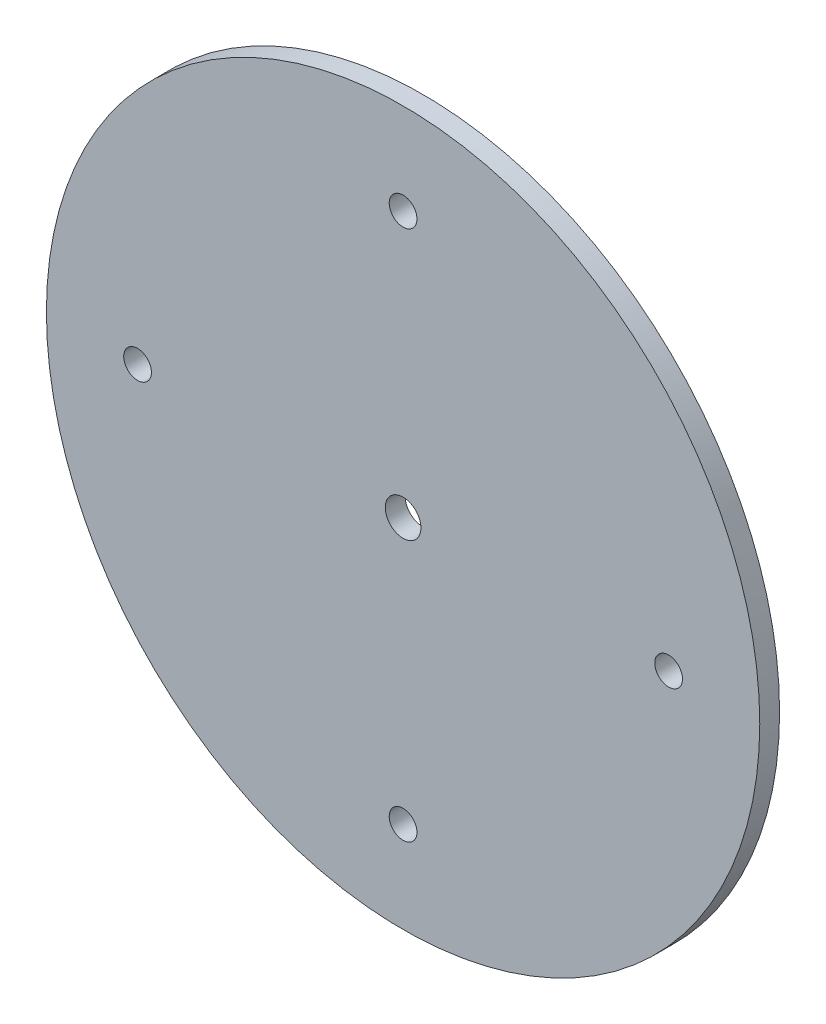
SolidWorks part; units mm, degrees
ref_plane "Front Plane" through (0, 0, 0) normal (0, 0, 1) x (1, 0, 0)
ref_plane "Top Plane" through (0, 0, 0) normal (0, 1, 0) x (1, 0, 0)
ref_plane "Right Plane" through (0, 0, 0) normal (1, 0, 0) x (0, 0, -1)
sketch "Sketch1" plane through (0, 0, 0) normal (0, 0, 1) x (1, 0, 0)
  line L0 (0, 0) -> (0, 33.5) construction
  line L1 (0, 33.5) -> (0, 45) construction
  circle A0 centre (0, 0) radius 45
  circle A1 centre (0, 0) radius 2.25
  circle A2 centre (0, 33.5) radius 1.75
  circle A3 centre (33.5, 0) radius 1.75
  circle A4 centre (0, -33.5) radius 1.75
  circle A5 centre (-33.5, 0) radius 1.75
  point P7 (0, 0)
  point P8 (0, 0)
  point P9 (0, 0)
  point P16 (0, 0)
  dimension "D1" = 3.5
  dimension "D2" = 4.5
  dimension "D3" = 90
  dimension "D4" = 33.5
  dimension "D5" = 4
extrude "Boss-Extrude1" add sketch "Sketch1" along normal blind 2.5
sketch "Sketch2" plane through (0, 0, 0) normal (0, 0, -1) x (-1, 0, 0)
  circle A0 centre (0, 0) radius 29.85
  circle A1 centre (0, 0) radius 12.65
  dimension "D1" = 59.7
  dimension "D2" = 25.3
extrude "Boss-Extrude2" add sketch "Sketch2" along normal blind 1
